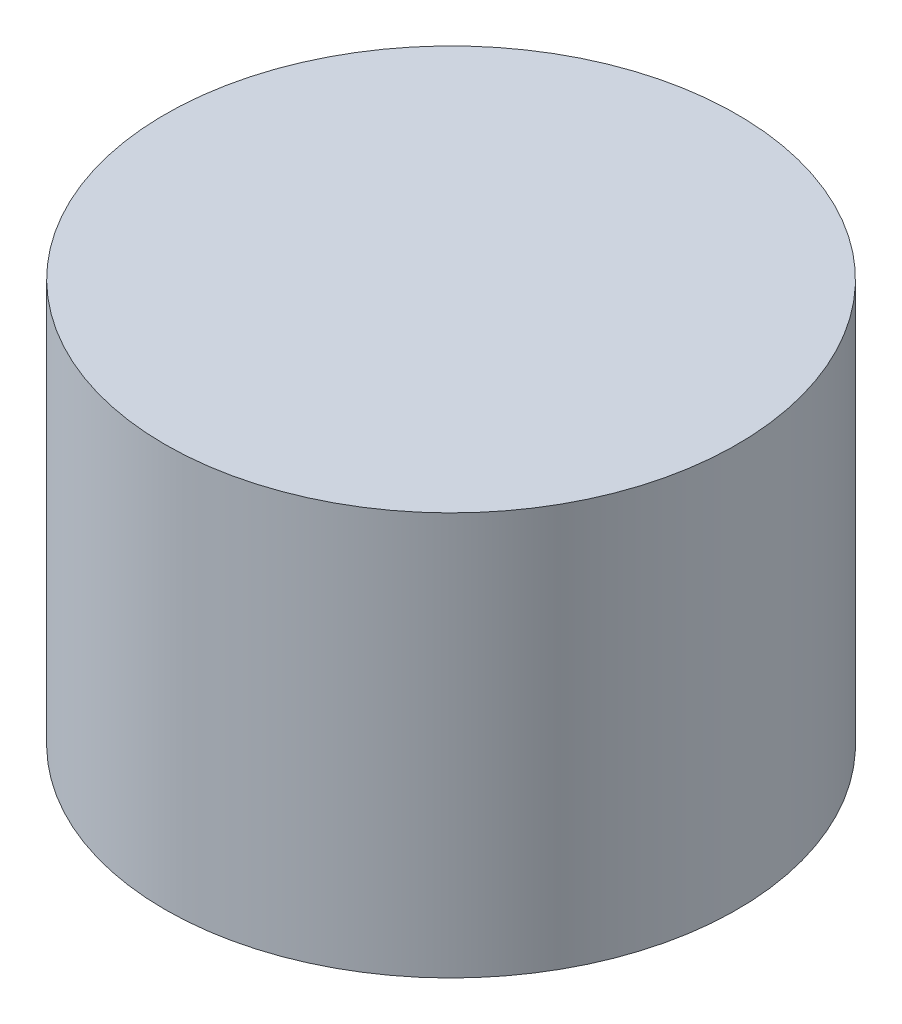
SolidWorks part; units mm, degrees
ref_plane "前视基准面" through (0, 0, 0) normal (0, 0, 1) x (1, 0, 0)
ref_plane "上视基准面" through (0, 0, 0) normal (0, 1, 0) x (1, 0, 0)
ref_plane "右视基准面" through (0, 0, 0) normal (1, 0, 0) x (0, 0, -1)
sketch "草图1" plane through (0, 0, 0) normal (0, 1, 0) x (1, 0, 0)
  circle A0 centre (0, 0) radius 7.1
  dimension "D1" = 14.2
extrude "凸台-拉伸1" add sketch "草图1" along normal blind 10
